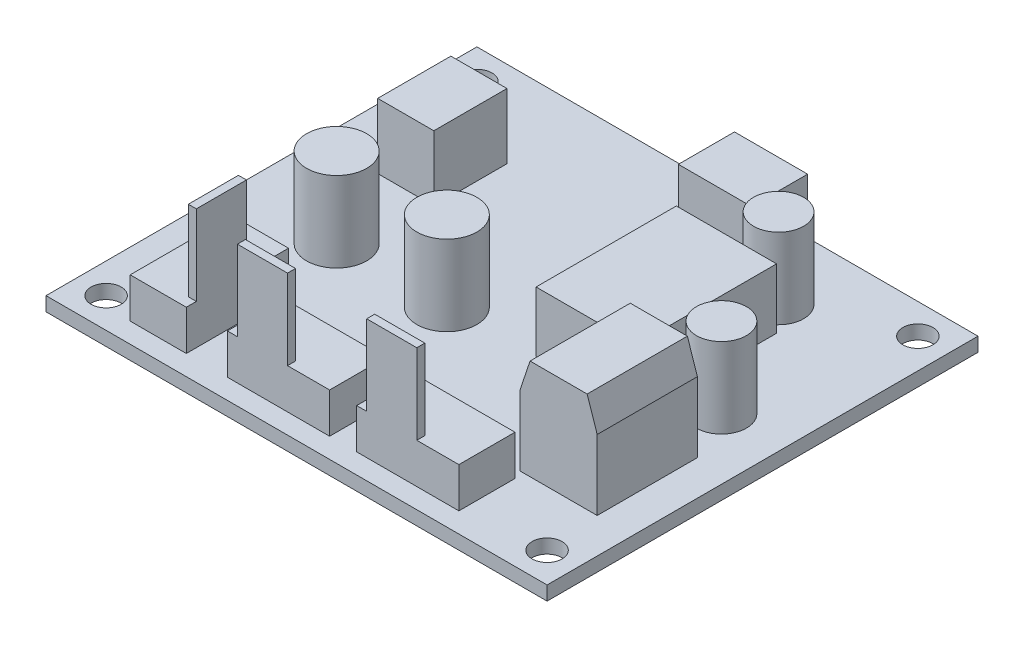
SolidWorks part; units mm, degrees
ref_plane "Plan de face" through (0, 0, 0) normal (0, 0, 1) x (1, 0, 0)
ref_plane "Plan de dessus" through (0, 0, 0) normal (0, 1, 0) x (1, 0, 0)
ref_plane "Plan de droite" through (0, 0, 0) normal (1, 0, 0) x (0, 0, -1)
sketch "Esquisse1" plane through (0, 0, 0) normal (0, 1, 0) x (1, 0, 0)
  line L0 (-25, 0) -> (0, 0) construction
  line L1 (-25, -21.5) -> (25, -21.5)
  line L2 (-25, -21.5) -> (-25, 21.5)
  line L3 (-25, 21.5) -> (25, 21.5)
  line L4 (25, -21.5) -> (25, 21.5)
  line L7 (0, 0) -> (0, 21.5) construction
  circle A0 centre (-22, 18.5) radius 1.5
  circle A1 centre (22, 18.5) radius 1.5
  circle A2 centre (22, -18.5) radius 1.5
  circle A3 centre (-22, -18.5) radius 1.5
  circle A4 centre (-22, 18.5) radius 3 construction
  dimension "D3" = 3
  dimension "D4" = 3
  dimension "D5" = 37
  dimension "D6" = 44
  dimension "D1" = 43
  dimension "D2" = 50
extrude "Boss.-Extru.1" add sketch "Esquisse1" along normal blind 1.4
sketch "Esquisse2" plane through (0, 0, 0) normal (0, 1, 0) x (1, 0, 0)
  line L0 (-25, -21.5) -> (25, -21.5) construction
  line L1 (-18.6, -9.3) -> (-13, -9.3)
  line L2 (-18.6, -9.3) -> (-18.6, -19.5)
  line L3 (-18.6, -19.5) -> (-13, -19.5)
  line L4 (-13, -9.3) -> (-13, -19.5)
  line L5 (-19, 12.9) -> (-13.4, 12.9)
  line L6 (-19, 12.9) -> (-19, 5.6)
  line L7 (-19, 5.6) -> (-13.4, 5.6)
  line L8 (-13.4, 12.9) -> (-13.4, 5.6)
  line L9 (1.7, 20.5) -> (9, 20.5)
  line L10 (1.7, 20.5) -> (1.7, 14.9)
  line L11 (1.7, 14.9) -> (9, 14.9)
  line L12 (9, 20.5) -> (9, 14.9)
  line L13 (13.8, -3) -> (21.5, -3)
  line L14 (13.8, -3) -> (13.8, -13)
  line L15 (13.8, -13) -> (21.5, -13)
  line L16 (21.5, -3) -> (21.5, -13)
  line L17 (14.2, -13.9) -> (4, -13.9)
  line L18 (14.2, -13.9) -> (14.2, -19.5)
  line L19 (14.2, -19.5) -> (4, -19.5)
  line L20 (4, -13.9) -> (4, -19.5)
  line L21 (1.3, -19.5) -> (-8.9, -19.5)
  line L22 (1.3, -19.5) -> (1.3, -13.9)
  line L23 (1.3, -13.9) -> (-8.9, -13.9)
  line L24 (-8.9, -19.5) -> (-8.9, -13.9)
  line L25 (25, -21.5) -> (25, 21.5) construction
  line L26 (25, 21.5) -> (-25, 21.5) construction
  line L27 (-25, 21.5) -> (-25, -21.5) construction
  line L29 (4.7, 11.7) -> (14.7, 11.7)
  line L30 (4.7, 11.7) -> (4.7, -2.3)
  line L31 (4.7, -2.3) -> (14.7, -2.3)
  line L32 (14.7, 11.7) -> (14.7, -2.3)
  dimension "D2" = 10.2
  dimension "D3" = 2
  dimension "D4" = 10.8
  dimension "D5" = 6
  dimension "D6" = 5.6
  dimension "D7" = 8.6
  dimension "D8" = 7.3
  dimension "D9" = 1
  dimension "D10" = 16
  dimension "D11" = 7.7
  dimension "D12" = 10
  dimension "D13" = 3.5
  dimension "D14" = 8.5
  dimension "D15" = 6.4
  dimension "D16" = 2.7
  dimension "D17" = 4.1
  dimension "D18" = 33.9
  dimension "D19" = 10
  dimension "D20" = 14
  dimension "D21" = 10.3
  dimension "D22" = 9.8
sketch "Esquisse3" plane through (0, 1.4, 0) normal (0, 1, 0) x (1, 0, 0)
  line L1 (-18.6, -9.3) -> (-13, -9.3)
  line L2 (-18.6, -9.3) -> (-18.6, -19.5)
  line L3 (-18.6, -19.5) -> (-13, -19.5)
  line L4 (-13, -9.3) -> (-13, -19.5)
  line L5 (-8.9, -13.9) -> (1.3, -13.9)
  line L6 (-8.9, -13.9) -> (-8.9, -19.5)
  line L7 (-8.9, -19.5) -> (1.3, -19.5)
  line L8 (1.3, -13.9) -> (1.3, -19.5)
  line L9 (4, -13.9) -> (14.2, -13.9)
  line L10 (4, -13.9) -> (4, -19.5)
  line L11 (4, -19.5) -> (14.2, -19.5)
  line L12 (14.2, -13.9) -> (14.2, -19.5)
extrude "Boss.-Extru.2" add sketch "Esquisse3" along normal blind 4 separate body
sketch "Esquisse4" plane through (0, 1.4, 0) normal (0, 1, 0) x (1, 0, 0)
  line L1 (-19, 12.9) -> (-13.4, 12.9)
  line L2 (-19, 12.9) -> (-19, 5.6)
  line L3 (-19, 5.6) -> (-13.4, 5.6)
  line L4 (-13.4, 12.9) -> (-13.4, 5.6)
  line L5 (1.7, 20.5) -> (9, 20.5)
  line L6 (1.7, 20.5) -> (1.7, 14.9)
  line L7 (1.7, 14.9) -> (9, 14.9)
  line L8 (9, 20.5) -> (9, 14.9)
extrude "Boss.-Extru.3" add sketch "Esquisse4" along normal blind 6.5 separate body
sketch "Esquisse5" plane through (0, 1.4, 0) normal (0, 1, 0) x (1, 0, 0)
  line L1 (4.7, 11.7) -> (14.7, 11.7)
  line L2 (4.7, 11.7) -> (4.7, -2.3)
  line L3 (4.7, -2.3) -> (14.7, -2.3)
  line L4 (14.7, 11.7) -> (14.7, -2.3)
extrude "Boss.-Extru.4" add sketch "Esquisse5" along normal blind 6 separate body
sketch "Esquisse6" plane through (0, 1.4, 0) normal (0, 1, 0) x (1, 0, 0)
  line L1 (13.8, -3) -> (21.5, -3)
  line L2 (13.8, -3) -> (13.8, -13)
  line L3 (13.8, -13) -> (21.5, -13)
  line L4 (21.5, -3) -> (21.5, -13)
extrude "Boss.-Extru.5" add sketch "Esquisse6" along normal blind 10 separate body
sketch "Esquisse7" plane through (0, 1.4, 0) normal (0, 1, 0) x (1, 0, 0)
  line L0 (4.7, 11.7) -> (14.7, 11.7) construction
  line L1 (14.7, 11.7) -> (14.7, -2.3) construction
  line L2 (21.5, -13) -> (21.5, -3) construction
  line L3 (21.5, -3) -> (13.8, -3) construction
  circle A0 centre (12.3, 14.3) radius 2.5
  circle A1 centre (18.9, 2) radius 2.5
  dimension "D1" = 5
  dimension "D2" = 2.6
  dimension "D3" = 2.4
  dimension "D4" = 2.6
  dimension "D5" = 5
extrude "Boss.-Extru.6" add sketch "Esquisse7" along normal blind 8 separate body
sketch "Esquisse8" plane through (0, 1.4, 0) normal (0, 1, 0) x (1, 0, 0)
  line L0 (-25, 21.5) -> (-25, -21.5) construction
  line L1 (-25, -21.5) -> (25, -21.5) construction
  circle A0 centre (-15, -2.5) radius 3
  circle A1 centre (-4, -2.5) radius 3
  dimension "D1" = 11
  dimension "D2" = 10
  dimension "D3" = 6
  dimension "D4" = 19
extrude "Boss.-Extru.7" add sketch "Esquisse8" along normal blind 8 separate body
sketch "Esquisse9" plane through (0, 5.4, 0) normal (0, 1, 0) x (1, 0, 0)
  line L1 (-13.8, -13.5) -> (-13, -13.5)
  line L2 (-13.8, -13.5) -> (-13.8, -18.5)
  line L3 (-13.8, -18.5) -> (-13, -18.5)
  line L4 (-13, -13.5) -> (-13, -18.5)
  line L5 (-8.9, -19.5) -> (1.3, -19.5) construction
  line L6 (-7.9, -19.5) -> (-2.9, -19.5)
  line L7 (-7.9, -19.5) -> (-7.9, -18.7)
  line L8 (-7.9, -18.7) -> (-2.9, -18.7)
  line L9 (-2.9, -19.5) -> (-2.9, -18.7)
  line L10 (4, -19.5) -> (14.2, -19.5) construction
  line L11 (5, -19.5) -> (10, -19.5)
  line L12 (5, -19.5) -> (5, -18.7)
  line L13 (5, -18.7) -> (10, -18.7)
  line L14 (10, -19.5) -> (10, -18.7)
  line L15 (-13, -19.5) -> (-13, -9.3) construction
  line L16 (5, -18.7) -> (4, -18.7) construction
  line L17 (4, -13.9) -> (4, -19.5) construction
  line L18 (-7.9, -18.7) -> (-8.9, -18.7) construction
  line L19 (-13.8, -19.5) -> (-13.8, -18.5) construction
  line L21 (-18.6, -19.5) -> (-13, -19.5) construction
  line L22 (-8.9, -13.9) -> (-8.9, -19.5) construction
  dimension "D1" = 1
  dimension "D2" = 5
  dimension "D3" = 0.8
extrude "Boss.-Extru.8" add sketch "Esquisse9" along normal blind 8
chamfer "Chanfrein1" distance 3 distance2 1 2 edges at (21.5, 11.4, 8) (13.8, 11.4, 8)
